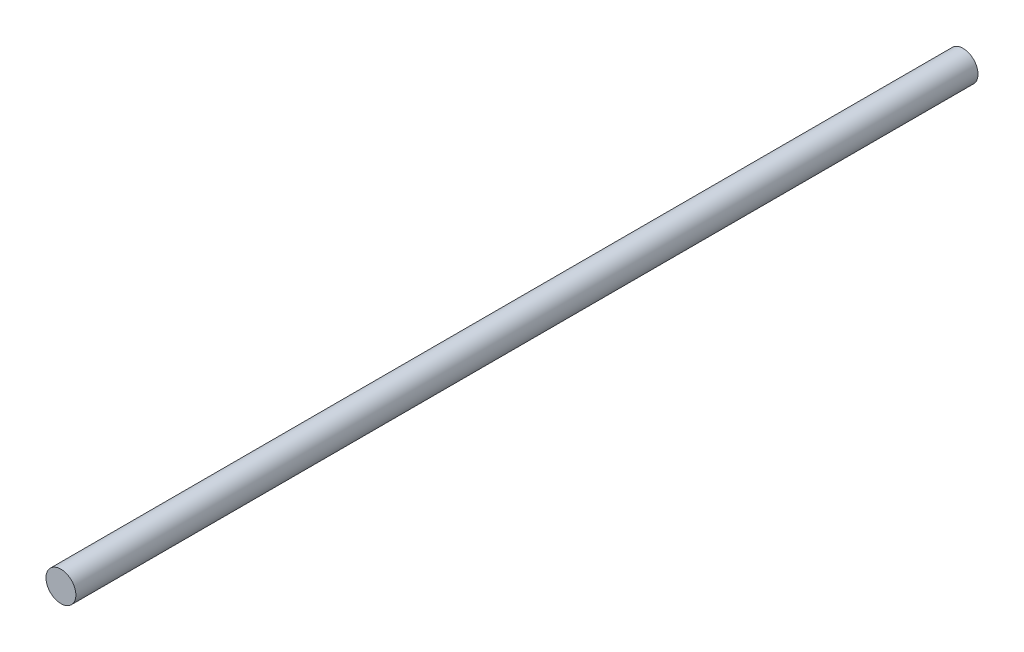
SolidWorks part; units mm, degrees
ref_plane "前视基准面" through (0, 0, 0) normal (0, 0, 1) x (1, 0, 0)
ref_plane "上视基准面" through (0, 0, 0) normal (0, 1, 0) x (1, 0, 0)
ref_plane "右视基准面" through (0, 0, 0) normal (1, 0, 0) x (0, 0, -1)
other "Configuration Table"
sketch "草图1" plane through (0, 0, 0) normal (0, 0, 1) x (1, 0, 0)
  circle A0 centre (0, 0) radius 2
  dimension "diameter" = 4
extrude "Cable_envelope" add sketch "草图1" along normal blind 120.7018
